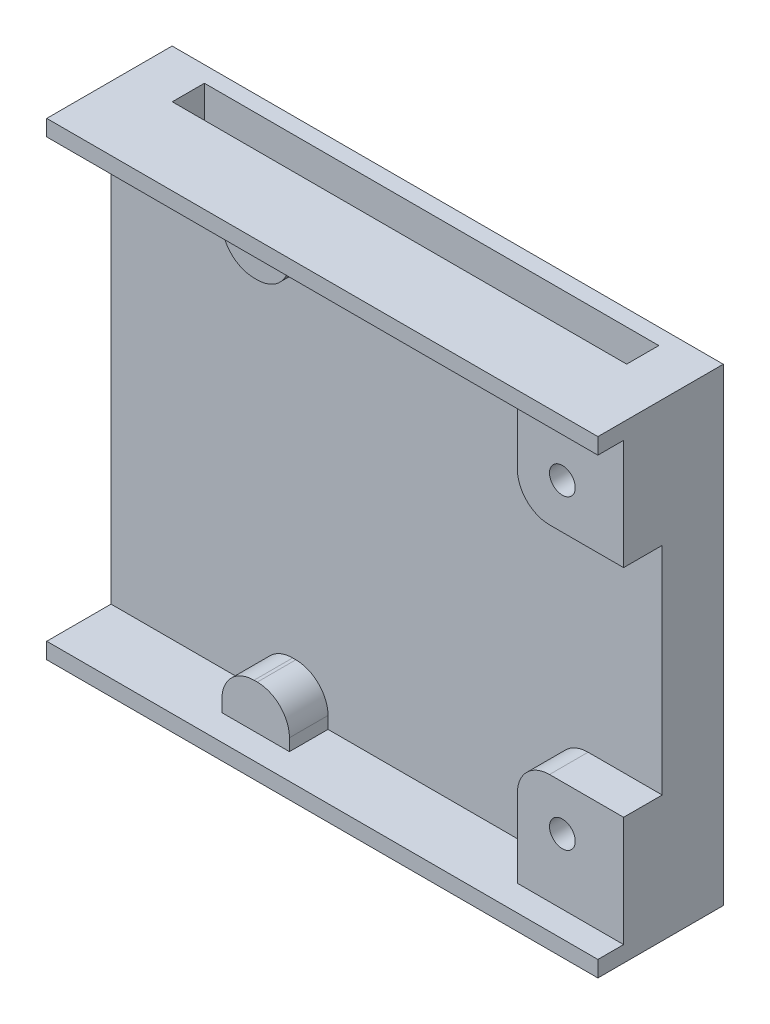
SolidWorks part; units mm, degrees
ref_plane "Front Plane" through (0, 0, 0) normal (1, 0, 0) x (0, 1, 0)
ref_plane "Top Plane" through (0, 0, 0) normal (0, 0, 1) x (0, 1, 0)
ref_plane "Right Plane" through (0, 0, 0) normal (0, 1, 0) x (-1, 0, 0)
sketch "Sketch2" plane through (0, 0, 0) normal (0, 0, 1) x (0, 1, 0)
  line L1 (-13.335, 17.145) -> (13.335, 17.145) construction
  line L2 (-13.335, 17.145) -> (-13.335, -17.145) construction
  line L3 (-13.335, -17.145) -> (13.335, -17.145) construction
  line L4 (13.335, 17.145) -> (13.335, -17.145) construction
  line L5 (-13.335, 17.145) -> (13.335, -17.145) construction
  line L6 (-13.335, -17.145) -> (13.335, 17.145) construction
  line L7 (-13.585, 17.145) -> (13.585, 17.145) construction
  line L8 (-13.585, 17.145) -> (-13.585, -17.145) construction
  line L9 (-13.585, -17.145) -> (13.585, -17.145) construction
  line L10 (13.585, 17.145) -> (13.585, -17.145) construction
  line L11 (-13.585, 17.145) -> (13.585, -17.145) construction
  line L12 (-13.585, -17.145) -> (13.585, 17.145) construction
  line L13 (-14.585, -17.145) -> (14.585, -17.145)
  line L14 (-14.585, -17.145) -> (-14.585, 17.145)
  line L15 (-14.585, 17.145) -> (14.585, 17.145)
  line L16 (14.585, -17.145) -> (14.585, 17.145)
  line L17 (-14.585, -17.145) -> (14.585, 17.145) construction
  line L18 (-14.585, 17.145) -> (14.585, -17.145) construction
  point P0 (0, 0)
  point P5 (0, 0)
  point P11 (0, 0)
  dimension "D1" = 26.67
  dimension "D2" = 34.29
  dimension "D3" = 0.25
  dimension "D4" = 1
extrude "Boss-Extrude1" add sketch "Sketch2" along normal blind 0.8 contours L13 L16 L15 L14
sketch "Sketch4" plane through (0, 0, 0.8) normal (0, 0, 1) x (1, 0, 0)
  line L0 (0, 0) -> (50000, 0) construction
  line L1 (17.145, -14.585) -> (17.145, 14.585) construction
  line L2 (-17.145, -13.585) -> (17.145, -13.585) construction
  line L3 (17.145, -13.585) -> (10.535, -13.585)
  line L4 (17.145, -13.585) -> (17.145, -6.725)
  line L5 (17.145, -6.725) -> (10.535, -6.725)
  line L6 (10.535, -13.585) -> (10.535, -6.725)
  line L7 (-7.845, -13.585) -> (-3.645, -13.585)
  line L8 (-7.845, -13.585) -> (-7.845, -10.835)
  line L9 (-7.845, -10.835) -> (-3.645, -10.835)
  line L10 (-3.645, -13.585) -> (-3.645, -10.835)
  line L12 (-17.145, -14.585) -> (-17.145, 14.585) construction
  line L13 (10.535, 13.585) -> (10.535, 6.725)
  line L14 (17.145, 6.725) -> (10.535, 6.725)
  line L15 (17.145, 13.585) -> (17.145, 6.725)
  line L16 (17.145, 13.585) -> (10.535, 13.585)
  line L17 (-3.645, 13.585) -> (-3.645, 10.835)
  line L18 (-7.845, 10.835) -> (-3.645, 10.835)
  line L19 (-7.845, 13.585) -> (-7.845, 10.835)
  line L20 (-7.845, 13.585) -> (-3.645, 13.585)
  circle A0 centre (13.335, -9.525) radius 1.2 construction
  circle A1 centre (13.335, 9.525) radius 1.2 construction
  line M14 (17.145, -14.585) -> (17.145, 14.585)
  dimension "D1" = 2.4
  dimension "D7" = 2.8
  dimension "D8" = 2.8
  dimension "D2" = 9.525
  dimension "D3" = 3.81
  dimension "D4" = 2.75
  dimension "D5" = 9.3
  dimension "D6" = 13.5
extrude "Boss-Extrude3" add sketch "Sketch4" along normal blind 2.4 contours L7 L10 L9 L8 | L6 L3 L5 M14 | L16 L13 L14 M14 | L20 L19 L18 L17
sketch "Sketch5" plane through (0, 0, 0.8) normal (0, 0, 1) x (1, 0, 0)
  line L1 (17.145, 13.585) -> (-17.145, 13.585)
  line L2 (17.145, 13.585) -> (17.145, 14.585)
  line L3 (17.145, 14.585) -> (-17.145, 14.585)
  line L4 (-17.145, 13.585) -> (-17.145, 14.585)
  line L5 (-17.145, -13.585) -> (17.145, -13.585)
  line L6 (-17.145, -13.585) -> (-17.145, -14.585)
  line L7 (-17.145, -14.585) -> (17.145, -14.585)
  line L8 (17.145, -13.585) -> (17.145, -14.585)
  line M1 (-3.645, -13.585) -> (-7.845, -13.585)
  line M8 (10.535, 13.585) -> (17.145, 13.585)
  line M9 (17.145, 13.585) -> (17.145, 14.585)
  line M10 (17.145, 14.585) -> (-17.145, 14.585)
  line M11 (-17.145, 14.585) -> (-17.145, -14.585)
  line M12 (-17.145, -14.585) -> (17.145, -14.585)
  line M13 (17.145, -14.585) -> (17.145, -13.585)
  line M14 (17.145, -13.585) -> (10.535, -13.585)
  line M18 (-7.845, 13.585) -> (-3.645, 13.585)
extrude "Boss-Extrude5" add sketch "Sketch5" along direction (0, 0, -1) on the side of the normal blind 4 contours L5 M11 M12 M13 M14 M1 | L1 M8 M9 M10 M11 M18
sketch "Sketch6" plane through (0, 0, 0) normal (0, 0, -1) x (1, 0, 0)
  line L0 (17.145, -14.585) -> (-17.145, -14.585) construction
  line L1 (-17.145, 14.585) -> (-14.135, 14.585)
  line L2 (-17.145, 14.585) -> (-17.145, -14.585)
  line L3 (-17.145, -14.585) -> (-14.135, -14.585)
  line L4 (-14.135, 14.585) -> (-14.135, -14.585)
  line L5 (0, 0) -> (50000, 0) construction
  line L6 (17.145, 14.585) -> (14.135, 14.585)
  line L7 (17.145, 14.585) -> (17.145, -14.585)
  line L8 (17.145, -14.585) -> (14.135, -14.585)
  line L9 (14.135, 14.585) -> (14.135, -14.585)
  circle A0 centre (13.335, 9.525) radius 0.8 construction
  line M9 (17.145, -14.585) -> (17.145, 14.585)
  line M10 (17.145, 14.585) -> (-17.145, 14.585)
  line M11 (-17.145, 14.585) -> (-17.145, -14.585)
  line M12 (-17.145, -14.585) -> (17.145, -14.585)
  dimension "D1" = 1.6
  dimension "D2" = 9.525
  dimension "D3" = 3.81
extrude "Boss-Extrude6" add sketch "Sketch6" along normal blind 2 contours L9 M10 M12 M9 | L4 M10 M11 M12
sketch "Sketch9" plane through (0, 0, -2) normal (0, 0, -1) x (1, 0, 0)
  line L1 (-17.145, 14.585) -> (17.145, 14.585)
  line L2 (-17.145, 14.585) -> (-17.145, -14.585)
  line L3 (-17.145, -14.585) -> (17.145, -14.585)
  line L4 (17.145, 14.585) -> (17.145, -14.585)
  line L9 (-14.135, 14.585) -> (-14.135, -14.585) construction
  line L10 (-14.135, 11.575) -> (14.135, 11.575)
  line L12 (-14.135, 11.575) -> (-14.135, -11.575)
  line L13 (-14.135, -11.575) -> (14.135, -11.575)
  line L14 (14.135, 11.575) -> (14.135, -11.575)
  line L15 (14.135, 14.585) -> (14.135, -14.585) construction
  line L16 (-14.135, 11.575) -> (-17.145, 11.575) construction
  line L17 (-14.135, 11.575) -> (-14.135, 14.585) construction
  line L18 (-14.135, -11.575) -> (-14.135, -14.585) construction
sketch "Sketch8" plane through (0, 0, 3.2) normal (0, 0, 1) x (1, 0, 0)
  line L0 (0, 0) -> (50000, 0) construction
  line L1 (17.145, -13.585) -> (17.145, -6.725) construction
  circle A0 centre (13.335, -9.525) radius 0.8
  circle A1 centre (13.335, 9.525) radius 0.8
  dimension "D1" = 1.6
  dimension "D2" = 9.525
  dimension "D3" = 3.81
extrude "Cut-Extrude1" cut sketch "Sketch8" against normal through all both and the other way through all contours A1 | A0
extrude "Boss-Extrude8" add sketch "Sketch9" along normal blind 1
fillet "Fillet1" radius 2 6 edges at (10.535, -6.725, 2) (10.535, 6.725, 2) (-3.645, 10.835, 2) (-7.845, 10.835, 2) (-7.845, -10.835, 2) (-3.645, -10.835, 2)
